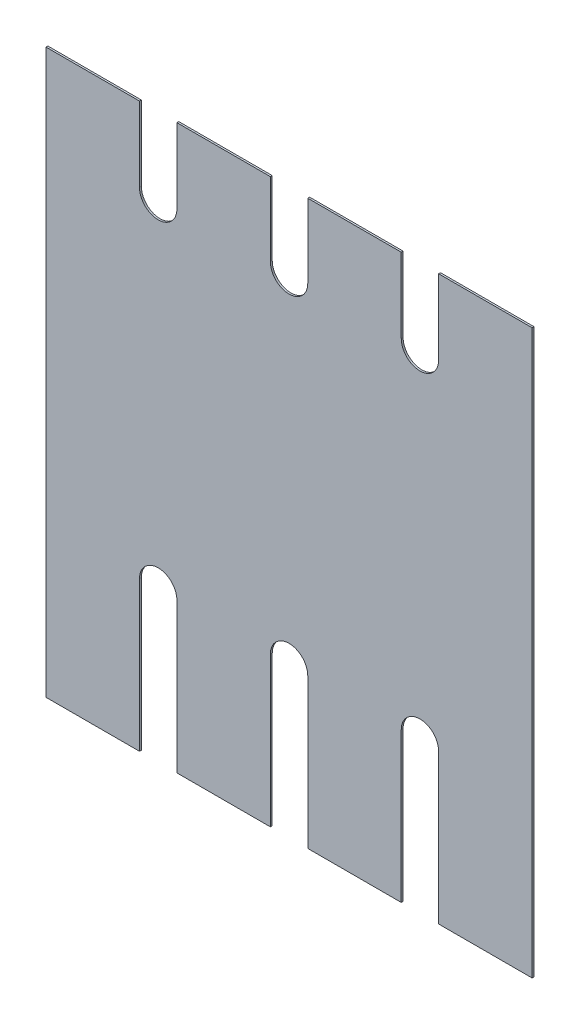
SolidWorks part; units mm, degrees
material "Kovar"
ref_plane "Front Plane" through (0, 0, 0) normal (0, 0, 1) x (1, 0, 0)
ref_plane "Top Plane" through (0, 0, 0) normal (0, 1, 0) x (1, 0, 0)
ref_plane "Right Plane" through (0, 0, 0) normal (1, 0, 0) x (0, 0, -1)
sketch "Sketch3" plane through (0, 0, 0) normal (0, 0, 1) x (1, 0, 0)
  line L0 (-1.75, 3.7501) -> (-1.75, 2.7501) construction
  line L1 (-3.25, 3.7501) -> (3.25, 3.7501)
  line L2 (-3.25, 3.7501) -> (-3.25, -3.7799)
  line L3 (-3.25, -3.7799) -> (3.25, -3.7799)
  line L4 (3.25, 3.7501) -> (3.25, -3.7799)
  line L5 (0.25, 3.7501) -> (0.25, 2.765)
  line L6 (0, 3.7501) -> (0, 2.765) construction
  line L7 (-0.25, 3.7501) -> (-0.25, 2.765)
  line L8 (-1.75, -3.7799) -> (-1.75, -1.7799) construction
  line L9 (-1.5, 3.7501) -> (-1.5, 2.7501)
  line L10 (-2, 3.7501) -> (-2, 2.7501)
  line L11 (0, -4.4165) -> (0, 4.4165) construction
  line L12 (1.75, 3.7501) -> (1.75, 2.7501) construction
  line L13 (1.5, 3.7501) -> (1.5, 2.7501)
  line L14 (2, 3.7501) -> (2, 2.7501)
  line L15 (0, -3.7799) -> (0, -1.7799) construction
  line L16 (-0.25, -3.7799) -> (-0.25, -1.7799)
  line L17 (0.25, -3.7799) -> (0.25, -1.7799)
  line L18 (1.75, -3.7799) -> (1.75, -1.7799) construction
  line L19 (-2, -3.7799) -> (-2, -1.7799)
  line L20 (-1.5, -3.7799) -> (-1.5, -1.7799)
  line L21 (2, -3.7799) -> (2, -1.7799)
  line L22 (1.5, -3.7799) -> (1.5, -1.7799)
  arc A0 (0.25, 3.7501) -> (-0.25, 3.7501) centre (0, 3.7501) ccw
  arc A1 (-0.25, 2.765) -> (0.25, 2.765) centre (0, 2.765) ccw
  arc A2 (-1.5, 3.7501) -> (-2, 3.7501) centre (-1.75, 3.7501) ccw
  arc A3 (-2, 2.7501) -> (-1.5, 2.7501) centre (-1.75, 2.7501) ccw
  arc A4 (1.5, 3.7501) -> (2, 3.7501) centre (1.75, 3.7501) cw
  arc A5 (2, 2.7501) -> (1.5, 2.7501) centre (1.75, 2.7501) cw
  arc A6 (-0.25, -3.7799) -> (0.25, -3.7799) centre (0, -3.7799) ccw
  arc A7 (0.25, -1.7799) -> (-0.25, -1.7799) centre (0, -1.7799) ccw
  arc A8 (-2, -3.7799) -> (-1.5, -3.7799) centre (-1.75, -3.7799) ccw
  arc A9 (-1.5, -1.7799) -> (-2, -1.7799) centre (-1.75, -1.7799) ccw
  arc A10 (2, -3.7799) -> (1.5, -3.7799) centre (1.75, -3.7799) cw
  arc A11 (1.5, -1.7799) -> (2, -1.7799) centre (1.75, -1.7799) cw
  point P6 (0, 3.2576)
  point P16 (-1.75, 3.2501)
  point P21 (0, -2.7799)
  point P28 (1.75, 3.2501)
  point P39 (-1.75, -2.7799)
  point P44 (1.75, -2.7799)
  dimension "D1" = 7.53
  dimension "D2" = 6.5
  dimension "D3" = 1.5
  dimension "D4" = 1.5
extrude "Boss-Extrude1" add sketch "Sketch3" along normal blind 0.025 contours L22 A11 L21 L3 L4 L1 L14 A5 L13 L5 A1 L7 L9 A3 L10 L2 L19 A9 L20 L16 A7 L17
